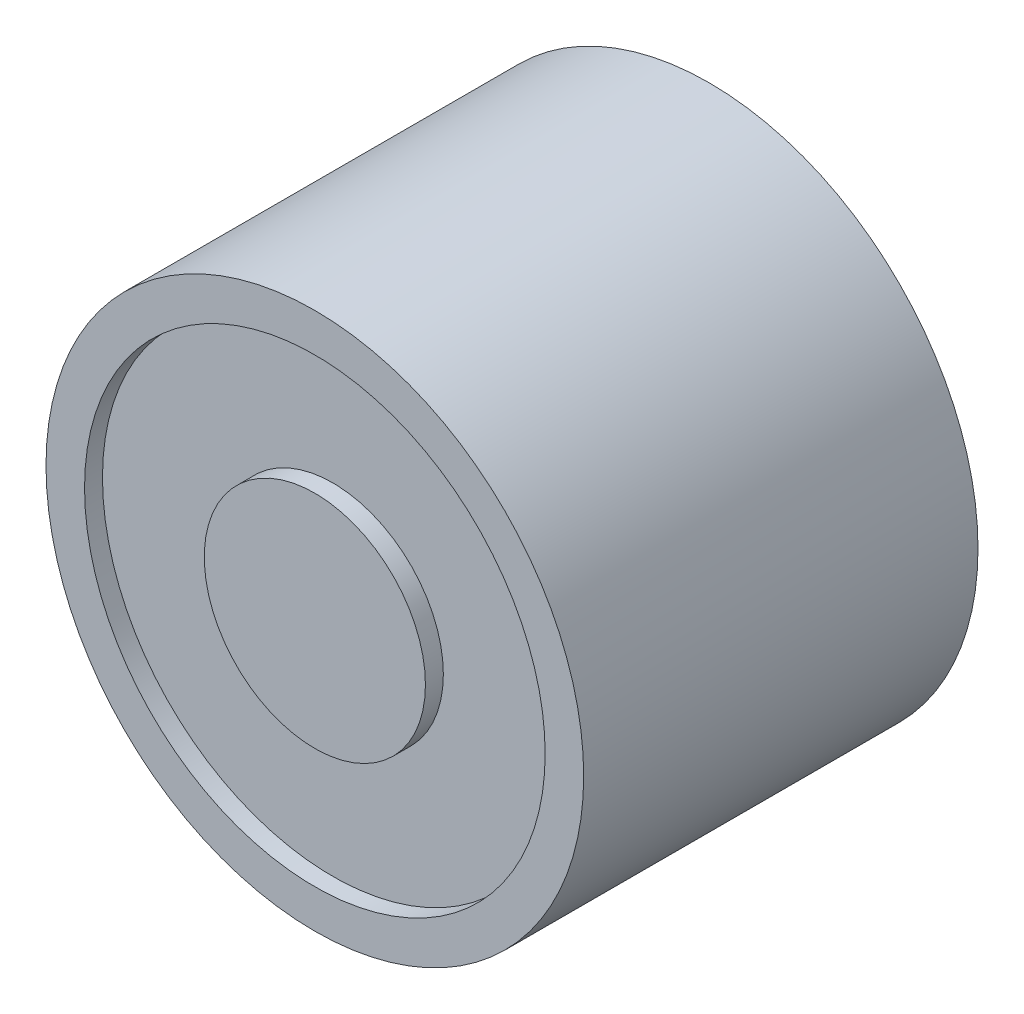
SolidWorks part; units mm, degrees
ref_plane "Front Plane" through (0, 0, 0) normal (0, 0, 1) x (1, 0, 0)
ref_plane "Top Plane" through (0, 0, 0) normal (0, 1, 0) x (1, 0, 0)
ref_plane "Right Plane" through (0, 0, 0) normal (1, 0, 0) x (0, 0, -1)
sketch "Sketch1" plane through (0, 0, 0) normal (0, 0, 1) x (1, 0, 0)
  circle A0 centre (0, 0) radius 15
  dimension "D1" = 30
extrude "Boss-Extrude1" add sketch "Sketch1" along normal blind 22
sketch "Sketch2" plane through (0, 0, 22) normal (0, 0, 1) x (1, 0, 0)
  circle A0 centre (0, 0) radius 6.17
  circle A1 centre (0, 0) radius 12.85
  dimension "D1" = 12.34
  dimension "D2" = 25.7
extrude "Cut-Extrude1" cut sketch "Sketch2" against normal blind 1
